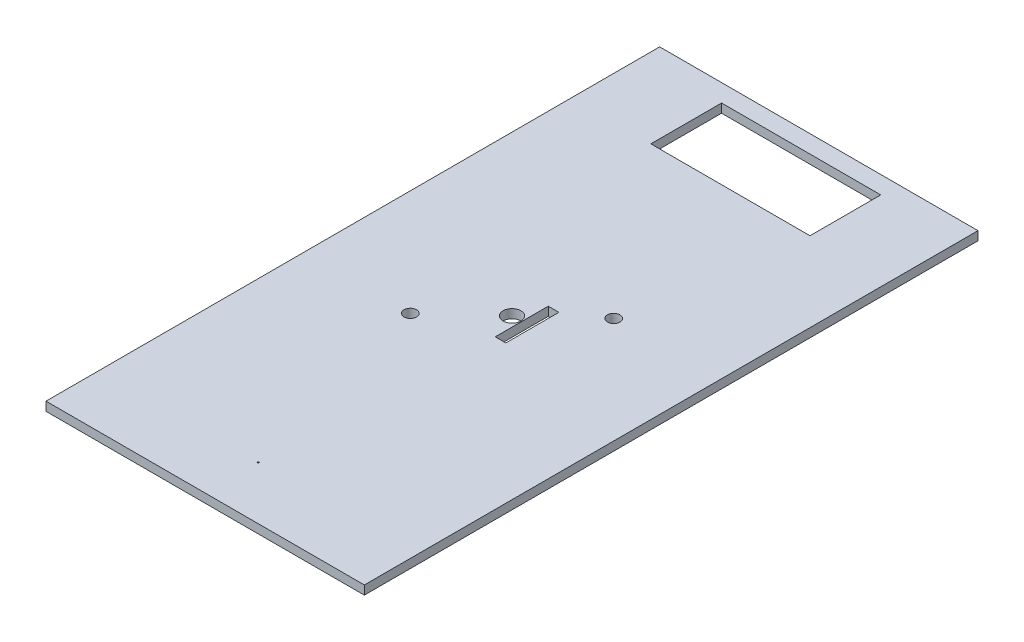
SolidWorks part; units mm, degrees
ref_plane "Plano frontal" through (0, 0, 0) normal (0, 0, 1) x (1, 0, 0)
ref_plane "Plano superior" through (0, 0, 0) normal (0, 1, 0) x (1, 0, 0)
ref_plane "Plano direito" through (0, 0, 0) normal (1, 0, 0) x (0, 0, -1)
sketch "Esboço1" plane through (0, 0, 0) normal (0, 1, 0) x (1, 0, 0)
  line L1 (90, -173.5) -> (-90, -173.5)
  line L2 (90, -173.5) -> (90, 173.5)
  line L3 (90, 173.5) -> (-90, 173.5)
  line L4 (-90, -173.5) -> (-90, 173.5)
  line L5 (90, -173.5) -> (-90, 173.5) construction
  line L6 (90, 173.5) -> (-90, -173.5) construction
  line L13 (-45, 163.5) -> (45, 163.5)
  line L14 (-45, 163.5) -> (-45, 123.5)
  line L15 (-45, 123.5) -> (45, 123.5)
  line L16 (45, 163.5) -> (45, 123.5)
  line L17 (-45, 163.5) -> (45, 123.5) construction
  line L18 (-45, 123.5) -> (45, 163.5) construction
  circle A0 centre (0, -143.5) radius 0.45
  circle A1 centre (0, 0) radius 5.05
  point P0 (0, 0)
  point P6 (0, 0)
  point P13 (0, 143.5)
  dimension "D5" = 0.9
  dimension "D3" = 10.1
  dimension "D1" = 347
  dimension "D2" = 180
  dimension "D6" = 30
  dimension "D7" = 90
  dimension "D8" = 40
  dimension "D9" = 90
  dimension "D10" = 30
  dimension "D11" = 90
extrude "Ressalto-extrusão1" add sketch "Esboço1" along normal blind 5
sketch "Esboço2" plane through (0, 5, 0) normal (0, 1, 0) x (1, 0, 0)
  line L0 (90, 173.5) -> (-90, 173.5) construction
  line L1 (5.5, 15) -> (11.5, 15)
  line L2 (5.5, 15) -> (5.5, -15)
  line L3 (5.5, -15) -> (11.5, -15)
  line L4 (11.5, 15) -> (11.5, -15)
  line L5 (5.5, 15) -> (11.5, -15) construction
  line L6 (5.5, -15) -> (11.5, 15) construction
  point P0 (8.5, 0)
  dimension "D1" = 9.5
  dimension "D2" = 30
  dimension "D3" = 6
  dimension "D4" = 158.5
extrude "Corte-extrusão1" cut sketch "Esboço2" against normal blind 10
sketch "Esboço3" plane through (0, 5, 0) normal (0, 1, 0) x (1, 0, 0)
  circle A0 centre (30, 27.5) radius 3.55
  circle A1 centre (-30, -27.5) radius 3.55
  dimension "D1" = 7.1
  dimension "D2" = 7.1
  dimension "D3" = 30
  dimension "D4" = 30
  dimension "D5" = 27.5
  dimension "D6" = 27.5
extrude "Corte-extrusão2" cut sketch "Esboço3" against normal blind 100
